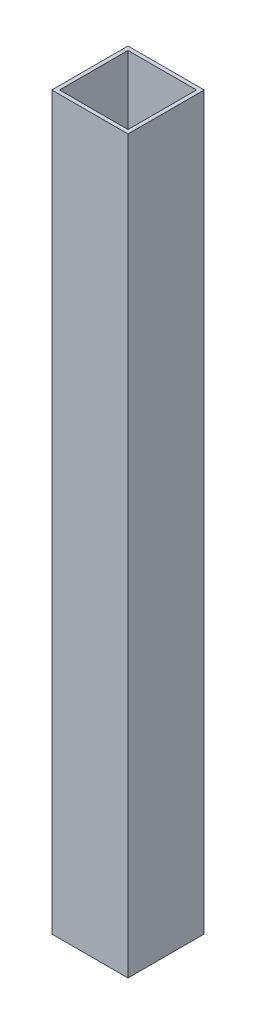
SolidWorks part; units mm, degrees
ref_plane "Front Plane" through (0, 0, 0) normal (0, 0, 1) x (1, 0, 0)
ref_plane "Top Plane" through (0, 0, 0) normal (0, 1, 0) x (1, 0, 0)
ref_plane "Right Plane" through (0, 0, 0) normal (1, 0, 0) x (0, 0, -1)
other "Configuration Table"
sketch "Sketch1" plane through (0, 0, 0) normal (0, 1, 0) x (1, 0, 0)
  line L1 (15.875, 15.875) -> (-15.875, 15.875)
  line L2 (15.875, 15.875) -> (15.875, -15.875)
  line L3 (15.875, -15.875) -> (-15.875, -15.875)
  line L4 (-15.875, 15.875) -> (-15.875, -15.875)
  line L5 (15.875, 15.875) -> (-15.875, -15.875) construction
  line L6 (15.875, -15.875) -> (-15.875, 15.875) construction
  line L7 (14.2875, -14.2875) -> (-14.2875, -14.2875)
  line L8 (14.2875, -14.2875) -> (14.2875, 14.2875)
  line L9 (14.2875, 14.2875) -> (-14.2875, 14.2875)
  line L10 (-14.2875, -14.2875) -> (-14.2875, 14.2875)
  line L11 (14.2875, -14.2875) -> (-14.2875, 14.2875) construction
  line L12 (14.2875, 14.2875) -> (-14.2875, -14.2875) construction
  point P0 (0, 0)
  point P6 (0, 0)
  dimension "D1" = 31.75
  dimension "D2" = 1.5875
extrude "Boss-Extrude1" add sketch "Sketch1" along normal blind 304.8
